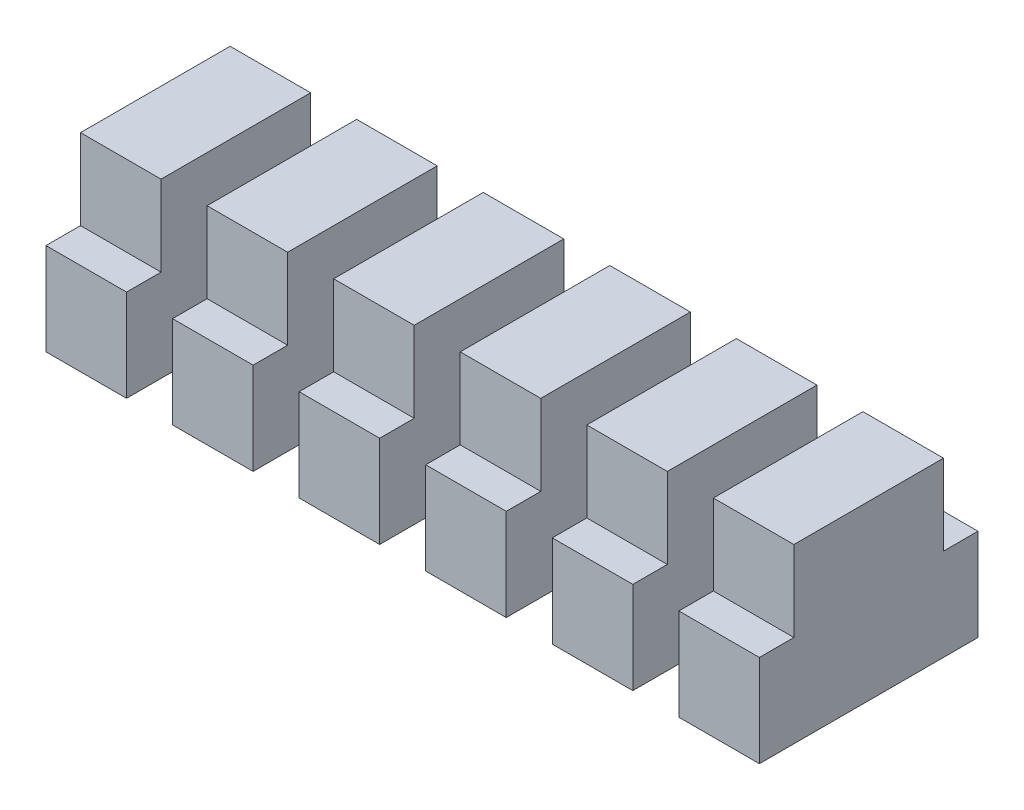
SolidWorks part; units mm, degrees
ref_plane "Front Plane" through (0, 0, 0) normal (0, 0, 1) x (1, 0, 0)
ref_plane "Top Plane" through (0, 0, 0) normal (0, 1, 0) x (1, 0, 0)
ref_plane "Right Plane" through (0, 0, 0) normal (1, 0, 0) x (0, 0, -1)
sketch "Sketch1" plane through (0, 0, 0) normal (0, 1, 0) x (1, 0, 0)
  line L0 (-13, 2.5) -> (-13, 9.5)
  line L1 (-31, -9.5) -> (-24, -9.5)
  line L2 (-31, -9.5) -> (-31, 9.5)
  line L3 (-31, 9.5) -> (-24, 9.5)
  line L4 (31, -9.5) -> (31, 9.5)
  line L5 (-31, -9.5) -> (31, 9.5) construction
  line L6 (-31, 9.5) -> (31, -9.5) construction
  line L7 (-24, 2.5) -> (-20, 2.5)
  line L8 (-24, 2.5) -> (-24, 9.5)
  line L9 (-9, 9.5) -> (-2, 9.5)
  line L10 (-20, 2.5) -> (-20, 9.5)
  line L11 (-13, 2.5) -> (-9, 2.5)
  line L12 (-9, 2.5) -> (-9, 9.5)
  line L13 (-2, 2.5) -> (-2, 9.5)
  line L14 (-2, 2.5) -> (2, 2.5)
  line L15 (2, 2.5) -> (2, 9.5)
  line L16 (9, 2.5) -> (9, 9.5)
  line L17 (9, 2.5) -> (13, 2.5)
  line L18 (13, 2.5) -> (13, 9.5)
  line L19 (20, 2.5) -> (20, 9.5)
  line L20 (20, 2.5) -> (24, 2.5)
  line L21 (24, 2.5) -> (24, 9.5)
  line L22 (-20, 9.5) -> (-13, 9.5)
  line L23 (2, 9.5) -> (9, 9.5)
  line L24 (13, 9.5) -> (20, 9.5)
  line L25 (24, 9.5) -> (31, 9.5)
  line L26 (-9, -9.5) -> (-9, -2.5)
  line L27 (-9, -9.5) -> (-2, -9.5)
  line L28 (-24, -9.5) -> (-24, -2.5)
  line L29 (-24, -2.5) -> (-20, -2.5)
  line L30 (-20, -9.5) -> (-20, -2.5)
  line L31 (-13, -9.5) -> (-13, -2.5)
  line L32 (-13, -2.5) -> (-9, -2.5)
  line L33 (2, -9.5) -> (2, -2.5)
  line L34 (-2, -9.5) -> (-2, -2.5)
  line L35 (-2, -2.5) -> (2, -2.5)
  line L36 (13, -9.5) -> (13, -2.5)
  line L37 (9, -9.5) -> (9, -2.5)
  line L38 (9, -2.5) -> (13, -2.5)
  line L39 (24, -9.5) -> (24, -2.5)
  line L40 (20, -9.5) -> (20, -2.5)
  line L41 (20, -2.5) -> (24, -2.5)
  line L42 (-20, -9.5) -> (-13, -9.5)
  line L43 (2, -9.5) -> (9, -9.5)
  line L44 (13, -9.5) -> (20, -9.5)
  line L45 (24, -9.5) -> (31, -9.5)
  point P0 (0, 0)
  point P6 (-24, 9.5)
  point P7 (-24, 2.5)
  point P9 (-20, 9.5)
  point P13 (-24, -9.5)
  point P30 (-20, -2.5)
  dimension "D1" = 62
  dimension "D2" = 19
  dimension "D3" = 7
  dimension "D4" = 4
  dimension "D5" = 7
  dimension "D7" = 7
  dimension "D6" = 5
  dimension "D8" = 5
extrude "Boss-Extrude1" add sketch "Sketch1" against normal blind 8
sketch "Sketch2" plane through (0, 0, 0) normal (0, 1, 0) x (1, 0, 0)
  line L0 (-31, 6.5) -> (-24, 6.5)
  line L1 (-31, -6.5) -> (-24, -6.5)
  line L2 (-20, 6.5) -> (-13, 6.5)
  line L3 (-9, 6.5) -> (-2, 6.5)
  line L4 (-24, 2.5) -> (-24, -2.5)
  line L5 (-9, -6.5) -> (-2, -6.5)
  line L6 (-20, 2.5) -> (-20, -2.5)
  line L7 (2, 6.5) -> (9, 6.5)
  line L8 (-13, 2.5) -> (-13, -2.5)
  line L9 (2, -6.5) -> (9, -6.5)
  line L10 (-9, 2.5) -> (-9, -2.5)
  line L11 (13, 6.5) -> (20, 6.5)
  line L12 (-2, 2.5) -> (-2, -2.5)
  line L13 (13, -6.5) -> (20, -6.5)
  line L14 (2, 2.5) -> (2, -2.5)
  line L15 (24, 6.5) -> (31, 6.5)
  line L16 (9, 2.5) -> (9, -2.5)
  line L17 (24, -6.5) -> (31, -6.5)
  line L18 (13, 2.5) -> (13, -2.5)
  line L20 (20, 2.5) -> (20, -2.5)
  line L22 (24, 2.5) -> (24, -2.5)
  line L23 (-20, -6.5) -> (-13, -6.5)
  line L44 (13, -9.5) -> (20, -9.5)
  line L45 (20, -9.5) -> (20, -2.5)
  line L46 (20, -2.5) -> (24, -2.5)
  line L47 (24, -2.5) -> (24, -9.5)
  line L48 (24, -9.5) -> (31, -9.5)
  line L49 (31, -9.5) -> (31, 9.5)
  line L50 (31, 9.5) -> (24, 9.5)
  line L51 (24, 9.5) -> (24, 2.5)
  line L52 (24, 2.5) -> (20, 2.5)
  line L53 (20, 2.5) -> (20, 9.5)
  line L54 (20, 9.5) -> (13, 9.5)
  line L55 (13, 9.5) -> (13, 2.5)
  line L56 (13, 2.5) -> (9, 2.5)
  line L57 (9, 2.5) -> (9, 9.5)
  line L58 (9, 9.5) -> (2, 9.5)
  line L59 (2, 9.5) -> (2, 2.5)
  line L60 (2, 2.5) -> (-2, 2.5)
  line L61 (-2, 2.5) -> (-2, 9.5)
  line L62 (-2, 9.5) -> (-9, 9.5)
  line L63 (-9, 9.5) -> (-9, 2.5)
  line L64 (-9, 2.5) -> (-13, 2.5)
  line L65 (-13, 2.5) -> (-13, 9.5)
  line L66 (-13, 9.5) -> (-20, 9.5)
  line L67 (-20, 9.5) -> (-20, 2.5)
  line L68 (-20, 2.5) -> (-24, 2.5)
  line L69 (-24, 2.5) -> (-24, 9.5)
  line L70 (-24, 9.5) -> (-31, 9.5)
  line L71 (-31, 9.5) -> (-31, -9.5)
  line L72 (-31, -9.5) -> (-24, -9.5)
  line L73 (-24, -9.5) -> (-24, -2.5)
  line L74 (-24, -2.5) -> (-20, -2.5)
  line L75 (-20, -2.5) -> (-20, -9.5)
  line L76 (-20, -9.5) -> (-13, -9.5)
  line L77 (-13, -9.5) -> (-13, -2.5)
  line L78 (-13, -2.5) -> (-9, -2.5)
  line L79 (-9, -2.5) -> (-9, -9.5)
  line L80 (-9, -9.5) -> (-2, -9.5)
  line L81 (-2, -9.5) -> (-2, -2.5)
  line L82 (-2, -2.5) -> (2, -2.5)
  line L83 (2, -2.5) -> (2, -9.5)
  line L84 (2, -9.5) -> (9, -9.5)
  line L85 (9, -9.5) -> (9, -2.5)
  line L86 (9, -2.5) -> (13, -2.5)
  line L87 (13, -2.5) -> (13, -9.5)
  line L89 (20, -6.5) -> (20, -2.5)
  line L91 (24, -2.5) -> (24, -6.5)
  line L93 (31, -6.5) -> (31, 6.5)
  line L95 (24, 6.5) -> (24, 2.5)
  line L97 (20, 2.5) -> (20, 6.5)
  line L99 (13, 6.5) -> (13, 2.5)
  line L101 (9, 2.5) -> (9, 6.5)
  line L103 (2, 6.5) -> (2, 2.5)
  line L105 (-2, 2.5) -> (-2, 6.5)
  line L107 (-9, 6.5) -> (-9, 2.5)
  line L109 (-13, 2.5) -> (-13, 6.5)
  line L111 (-20, 6.5) -> (-20, 2.5)
  line L113 (-24, 2.5) -> (-24, 6.5)
  line L115 (-31, 6.5) -> (-31, -6.5)
  line L117 (-24, -6.5) -> (-24, -2.5)
  line L119 (-20, -2.5) -> (-20, -6.5)
  line L121 (-13, -6.5) -> (-13, -2.5)
  line L123 (-9, -2.5) -> (-9, -6.5)
  line L125 (-2, -6.5) -> (-2, -2.5)
  line L127 (2, -2.5) -> (2, -6.5)
  line L129 (9, -6.5) -> (9, -2.5)
  line L131 (13, -2.5) -> (13, -6.5)
  point P41 (-31, 6.5)
  point P45 (31, 6.5)
  point P46 (-31, -6.5)
  point P47 (31, -6.5)
  dimension "D1" = 0
extrude "Boss-Extrude2" add sketch "Sketch2" along normal blind 7
